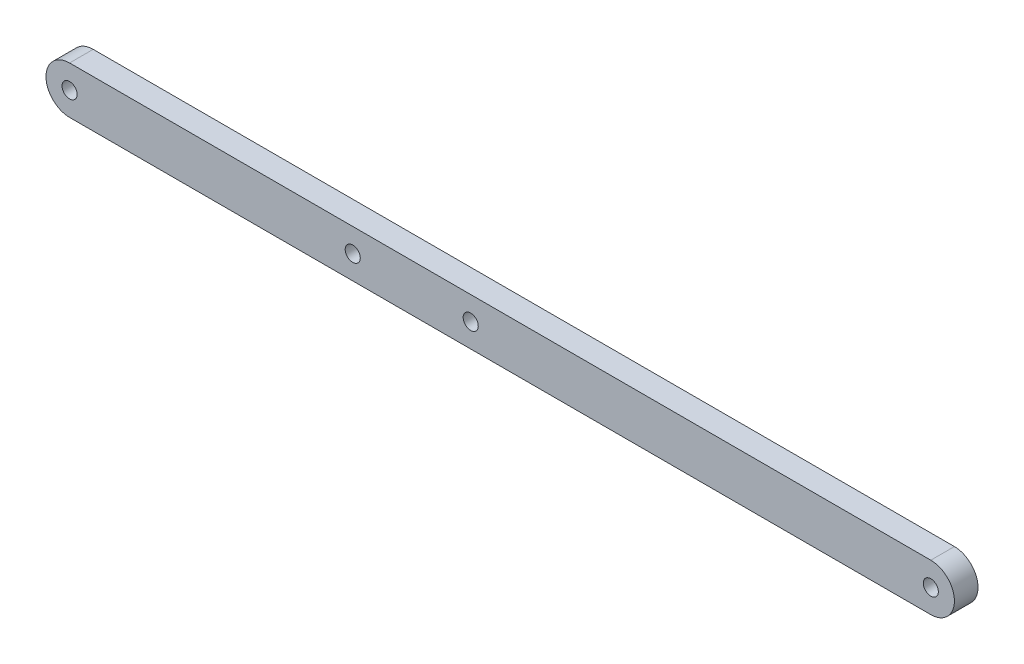
SolidWorks part; units mm, degrees
ref_plane "Front Plane" through (0, 0, 0) normal (0, 0, 1) x (1, 0, 0)
ref_plane "Top Plane" through (0, 0, 0) normal (0, 1, 0) x (1, 0, 0)
ref_plane "Right Plane" through (0, 0, 0) normal (1, 0, 0) x (0, 0, -1)
sketch "Sketch2" plane through (0, 0, 0) normal (0, 0, 1) x (1, 0, 0)
  line L0 (0, 0) -> (231.775, 0) construction
  line L1 (0, 6.35) -> (231.775, 6.35)
  line L2 (0, -6.35) -> (231.775, -6.35)
  arc A0 (0, 6.35) -> (0, -6.35) centre (0, 0) ccw
  arc A1 (231.775, -6.35) -> (231.775, 6.35) centre (231.775, 0) ccw
  circle A2 centre (0, 0) radius 2.032
  circle A3 centre (231.775, 0) radius 2.032
  circle A4 centre (76.2, 0) radius 2.032
  circle A5 centre (107.95, 0) radius 2.032
  point P3 (115.8875, 0)
  dimension "D3" = 4.064
  dimension "D4" = 76.2
  dimension "D5" = 4.064
  dimension "D6" = 107.95
  dimension "D1" = 231.775
  dimension "D2" = 12.7
extrude "Boss-Extrude1" add sketch "Sketch2" along normal mid plane 6.35
